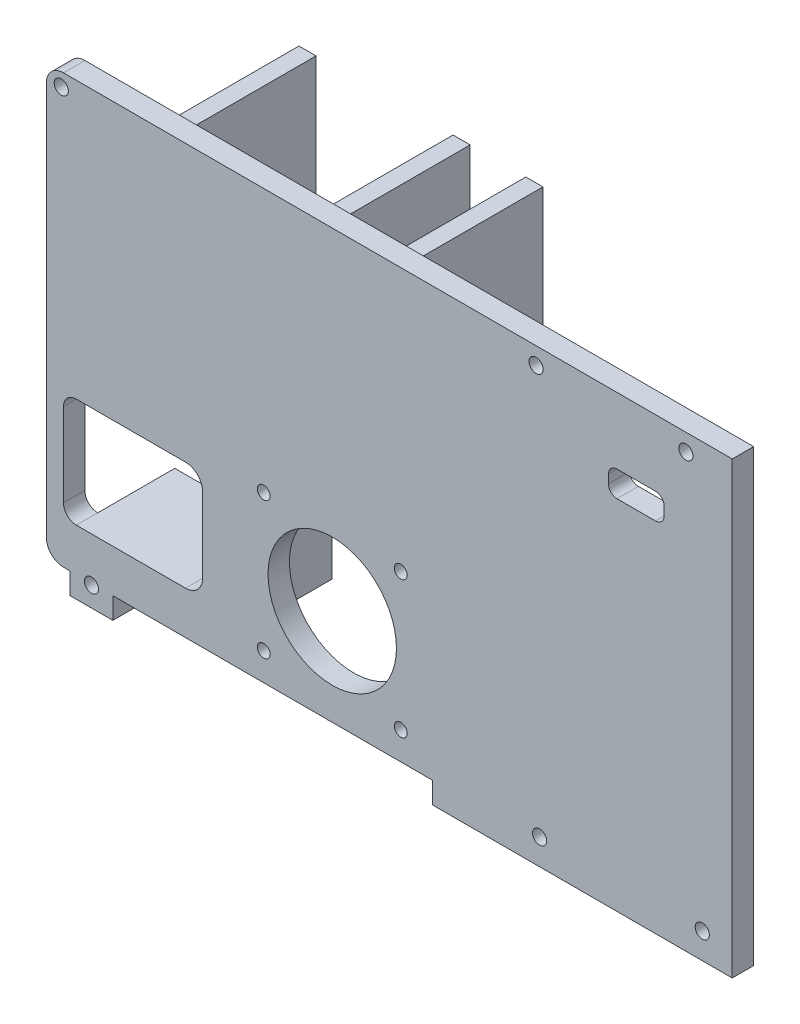
SolidWorks part; units mm, degrees
ref_plane "前视基准面" through (0, 0, 0) normal (0, 0, 1) x (1, 0, 0)
ref_plane "上视基准面" through (0, 0, 0) normal (0, 1, 0) x (1, 0, 0)
ref_plane "右视基准面" through (0, 0, 0) normal (1, 0, 0) x (0, 0, -1)
sketch "草图1" plane through (0, 0, 0) normal (0, 0, 1) x (1, 0, 0)
  line L20 (105.215, -55) -> (105.215, 50)
  line L21 (105.215, 50) -> (-51, 50)
  line L22 (-55, 46) -> (-55, -46)
  line L23 (-51, -50) -> (-49.4681, -50)
  line L24 (-49.4681, -50) -> (-49.4681, -55)
  line L25 (-49.4681, -55) -> (-39.4681, -55)
  line L26 (-39.4681, -55) -> (-39.4681, -50)
  line L27 (-39.4681, -50) -> (35.215, -50)
  line L28 (35.215, -50) -> (35.215, -55)
  line L29 (35.215, -55) -> (105.215, -55)
  arc A4 (-51, 50) -> (-55, 46) centre (-51, 46) ccw
  arc A5 (-55, -46) -> (-51, -50) centre (-51, -46) ccw
extrude "凸台-拉伸1" add sketch "草图1" along normal blind 5
sketch "草图2" plane through (0, 0, 0) normal (0, 0, -1) x (-1, 0, 0)
  line L1 (37, 41.933) -> (33, 41.933)
  line L5 (37, 41.933) -> (37, 1.933)
  line L7 (37, 1.933) -> (33, 1.933)
  line L11 (33, 41.933) -> (33, 1.933)
  line L16 (1, 41.933) -> (-3, 41.933)
  line L17 (1, 41.933) -> (1, 1.933)
  line L18 (1, 1.933) -> (-3, 1.933)
  line L19 (-3, 41.933) -> (-3, 1.933)
  line L20 (-16, 41.933) -> (-20, 41.933)
  line L21 (-16, 41.933) -> (-16, 1.933)
  line L22 (-16, 1.933) -> (-20, 1.933)
  line L23 (-20, 41.933) -> (-20, 1.933)
  dimension "D2" = 4
  dimension "D3" = 4
  dimension "D4" = 4
  dimension "D5" = 40
  dimension "D6" = 40
  dimension "D7" = 40
  dimension "D8" = 32
  dimension "D11" = 13
extrude "凸台-拉伸2" add sketch "草图2" along normal blind 36
ref_plane "基准面1" through (0, 20, 0) normal (0, 1, 0) x (1, 0, 0)
sketch "草图3" plane through (0, 20, 0) normal (0, 1, 0) x (1, 0, 0)
  line L0 (-49.4681, 0) -> (-37, 12.4681)
  line L1 (-37, 36) -> (-37, 0) construction
  line L2 (-33, 12.4681) -> (-24.5319, 0)
  line L3 (-33, 36) -> (-33, 0) construction
  line L4 (105.215, 0) -> (-51, 0) construction
  line L5 (-1, 12.4681) -> (-8.7559, 0)
  line L6 (-1, 36) -> (-1, 0) construction
  line L7 (20, 12.4681) -> (30.6738, 0)
  line L8 (20, 36) -> (20, 0) construction
  line L9 (3, 12.4681) -> (9.4364, 0)
  line L10 (3, 36) -> (3, 0) construction
  line L11 (9.4364, 0) -> (16, 12.4681)
  line L12 (16, 36) -> (16, 0) construction
  line L13 (3, 36) -> (3, 0)
  line L14 (105.215, 0) -> (-51, 0)
  line L15 (20, 36) -> (20, 0)
  line L20 (16, 0) -> (20, 0)
  line L21 (20, 0) -> (20, 36)
  line L22 (20, 36) -> (16, 36)
  line L23 (16, 36) -> (16, 0)
  line L24 (16, 0) -> (20, 0)
  line L25 (20, 0) -> (20, 36)
  line L26 (20, 36) -> (16, 36)
  line L27 (16, 36) -> (16, 0)
  line L28 (-1, 0) -> (3, 0)
  line L29 (3, 0) -> (3, 36)
  line L30 (3, 36) -> (-1, 36)
  line L31 (-1, 36) -> (-1, 0)
  line L32 (-1, 0) -> (3, 0)
  line L33 (3, 0) -> (3, 36)
  line L34 (3, 36) -> (-1, 36)
  line L35 (-1, 36) -> (-1, 0)
  line L36 (-37, 0) -> (-33, 0)
  line L37 (-33, 0) -> (-33, 36)
  line L38 (-33, 36) -> (-37, 36)
  line L39 (-37, 36) -> (-37, 0)
  line L40 (-37, 0) -> (-33, 0)
  line L41 (-33, 0) -> (-33, 36)
  line L42 (-33, 36) -> (-37, 36)
  line L43 (-37, 36) -> (-37, 0)
  dimension "D1" = 0
  dimension "D2" = 0
  dimension "D3" = 0
extrude "凸台-拉伸3" add sketch "草图3" along normal mid plane 15 contours L7 L15 L14 | L27 L11 L14 | L14 L9 L13 | L35 L5 L14 | L41 L14 L2 | L43 L0 L14
sketch "草图4" plane through (0, 0, 0) normal (0, 0, -1) x (-1, 0, 0)
  line L12 (18.5, -18.5) -> (18.5, -36)
  line L17 (-11, -40) -> (48, -40)
  line L18 (-14, -17.5) -> (-14, -37)
  line L19 (48, -14.5) -> (-11, -14.5)
  line L20 (51, -37) -> (51, -17.5)
  line L21 (22.5, -40) -> (48, -40)
  line L23 (48, -14.5) -> (22.5, -14.5)
  line L24 (51, -37) -> (51, -17.5)
  arc A4 (18.5, -36) -> (22.5, -40) centre (22.5, -36) ccw
  arc A5 (18.5, -18.5) -> (22.5, -14.5) centre (22.5, -18.5) cw
  arc A8 (-14, -37) -> (-11, -40) centre (-11, -37) ccw
  arc A9 (-11, -14.5) -> (-14, -17.5) centre (-11, -17.5) ccw
  arc A10 (51, -17.5) -> (48, -14.5) centre (48, -17.5) ccw
  arc A11 (48, -40) -> (51, -37) centre (48, -37) ccw
  arc A14 (51, -17.5) -> (48, -14.5) centre (48, -17.5) ccw
  arc A15 (48, -40) -> (51, -37) centre (48, -37) ccw
  dimension "D2" = 4
  dimension "D1" = 0
extrude "切除-拉伸2" cut sketch "草图4" against normal blind 14
sketch "草图5" plane through (0, 0, 0) normal (0, 0, -1) x (-1, 0, 0)
  line L0 (-46, -13.5) -> (48, -13.5) construction
  line L1 (-46, -13.5) -> (-41, -13.5)
  line L3 (18.5, -18.5) -> (18.5, -36) construction
  line L5 (-41, -41) -> (-46, -41)
  line L6 (18.5, -18.5) -> (18.5, -36)
  line L7 (-46, -13.5) -> (-41, -13.5)
  line L8 (-46, -13.5) -> (-46, -41)
  line L9 (-46, -41) -> (-41, -41)
  line L10 (-41, -13.5) -> (-41, -41)
  line L14 (11.223, -13.5) -> (11.223, -41)
  line L15 (48, -14.5) -> (22.5, -14.5) construction
  line L16 (48, -14.5) -> (22.5, -14.5)
  line L17 (22.5, -40) -> (48, -40) construction
  line L18 (22.5, -40) -> (48, -40)
  line L21 (48, -14.5) -> (48, -10.5)
  line L22 (48, -10.5) -> (11.223, -10.5)
  line L23 (11.223, -10.5) -> (11.223, -13.5)
  line L24 (48, -40) -> (48, -44)
  line L25 (48, -44) -> (11.223, -44)
  line L26 (11.223, -44) -> (11.223, -41)
  arc A0 (18.5, -36) -> (22.5, -40) centre (22.5, -36) ccw construction
  arc A1 (18.5, -36) -> (22.5, -40) centre (22.5, -36) ccw
  arc A2 (22.5, -14.5) -> (18.5, -18.5) centre (22.5, -18.5) ccw construction
  arc A3 (22.5, -14.5) -> (18.5, -18.5) centre (22.5, -18.5) ccw
  dimension "D1" = 4
  dimension "D2" = 5
  dimension "D4" = 4
extrude "凸台-拉伸4" add sketch "草图5" along normal blind 18
sketch "草图6" plane through (0, 0, 0) normal (0, 0, -1) x (-1, 0, 0)
  line L0 (11.223, -10.5) -> (11.223, -44) construction
  line L1 (4.223, -43.5) -> (-27.777, -43.5) construction
  line L2 (4.223, -43.5) -> (4.223, -11.5) construction
  line L3 (4.223, -11.5) -> (-27.777, -11.5) construction
  line L4 (-27.777, -43.5) -> (-27.777, -11.5) construction
  line L5 (4.223, -43.5) -> (-27.777, -11.5) construction
  line L6 (4.223, -11.5) -> (-27.777, -43.5) construction
  line L8 (39.4681, -50) -> (-35.215, -50) construction
  circle A0 centre (-11.777, -27.5) radius 15
  circle A1 centre (4.223, -43.5) radius 1.5
  circle A2 centre (4.223, -11.5) radius 1.5
  circle A3 centre (-27.777, -11.5) radius 1.5
  circle A4 centre (-27.777, -43.5) radius 1.5
  point P0 (-11.777, -27.5)
  point P15 (-10.777, -29)
  point P16 (-10.777, -27.5)
  dimension "D4" = 30
  dimension "D5" = 3
  dimension "D6" = 3
  dimension "D7" = 3
  dimension "D8" = 3
  dimension "D1" = 32
  dimension "D2" = 7
  dimension "D3" = 6.5
extrude "切除-拉伸3" cut sketch "草图6" against normal blind 18
sketch "草图7" plane through (0, 0, 5) normal (0, 0, 1) x (1, 0, 0)
  line L6 (76.2954, 28.5) -> (89.2954, 28.5) construction
  line L7 (78.2954, 28.5) -> (87.2954, 28.5)
  line L9 (89.2954, 28.5) -> (76.2954, 28.5)
  line L10 (89.2954, 30.5) -> (89.2954, 32.5)
  line L11 (87.2954, 34.5) -> (78.2954, 34.5)
  line L12 (76.2954, 30.5) -> (76.2954, 32.5)
  arc A0 (89.2954, 30.5) -> (87.2954, 28.5) centre (87.2954, 30.5) cw
  arc A1 (78.2954, 28.5) -> (76.2954, 30.5) centre (78.2954, 30.5) cw
  arc A2 (89.2954, 32.5) -> (87.2954, 34.5) centre (87.2954, 32.5) ccw
  arc A3 (78.2954, 34.5) -> (76.2954, 32.5) centre (78.2954, 32.5) ccw
  point P13 (89.2954, 34.5)
  dimension "D3" = 2
  dimension "D1" = 6
extrude "切除-拉伸4" cut sketch "草图7" along normal blind 15 and the other way blind 26 contours L7 A0 L10 A2 L11 A3 L12 A1
sketch "草图9" plane through (0, 0, 5) normal (0, 0, 1) x (1, 0, 0)
  circle A0 centre (-44.4681, -50.3601) radius 1.65 construction
  circle A1 centre (-51.5198, 46.8795) radius 1.65 construction
  circle A2 centre (60.215, -48.978) radius 1.65 construction
  circle A3 centre (59.3916, 46) radius 1.65 construction
  circle A4 centre (98.215, -48.978) radius 1.65 construction
  circle A5 centre (94.3916, 46) radius 1.65 construction
  circle A6 centre (-44.4681, -50.3601) radius 1.65
  circle A7 centre (-51.5198, 46.8795) radius 1.65
  circle A8 centre (60.215, -48.978) radius 1.65
  circle A9 centre (59.3916, 46) radius 1.65
  circle A10 centre (98.215, -48.978) radius 1.65
  circle A11 centre (94.3916, 46) radius 1.65
extrude "切除-拉伸5" cut sketch "草图9" against normal blind 41
ref_plane "基准面2" through (0, -30, 0) normal (0, 1, 0) x (1, 0, 0)
sketch "草图10" plane through (0, -30, 0) normal (0, 1, 0) x (1, 0, 0)
  line L0 (46, 14.7578) -> (55.4974, 0)
  line L1 (46, 18) -> (46, 0) construction
  line L2 (105.215, 0) -> (-51, 0) construction
rib "筋2" sketch "草图10" sketch "草图10" thickness 10 extrusion direction parallel to sketch draft on no parameters "D1"=10
sketch "草图11" plane through (46, 0, 0) normal (1, 0, 0) x (0, 0, -1)
  line L0 (18, -13.5) -> (0, -4.7735)
  line L1 (0, -55) -> (0, 50) construction
  line L2 (18, -13.5) -> (0, -13.5) construction
  line L3 (18, -13.5) -> (0, -13.5)
  line L4 (0, -13.5) -> (0, -4.7735)
extrude "凸台-拉伸6" add sketch "草图11" against normal up to surface (5 mm away) up to face at (41, -27.25, -9)
sketch "草图12" plane through (20, 0, 0) normal (1, 0, 0) x (0, 0, -1)
  line L0 (0, 12.5) -> (0, 1.933) construction
  line L1 (36, 1.933) -> (0, 1.933)
  line L2 (36, 1.933) -> (36, 6.933)
  line L3 (36, 6.933) -> (0, 6.933)
  line L4 (0, 1.933) -> (0, 6.933)
  dimension "D1" = 5
extrude "切除-拉伸6" cut sketch "草图12" against normal blind 87
